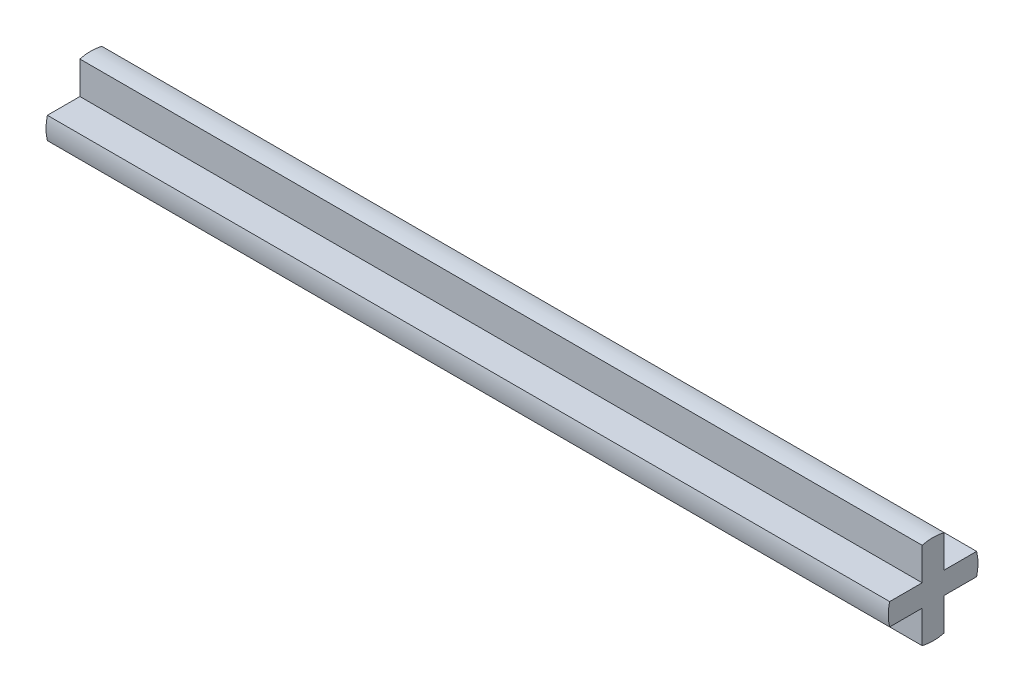
SolidWorks part; units mm, degrees
ref_plane "前视基准面" through (0, 0, 0) normal (0, 0, 1) x (1, 0, 0)
ref_plane "上视基准面" through (0, 0, 0) normal (0, 1, 0) x (1, 0, 0)
ref_plane "右视基准面" through (0, 0, 0) normal (1, 0, 0) x (0, 0, -1)
sketch "草图1" plane through (0, 0, 0) normal (1, 0, 0) x (0, 0, -1)
  circle A0 centre (0, 0) radius 2.45
extrude "凸台-拉伸1" add sketch "草图1" along normal mid plane 46
sketch "草图2" plane through (23, 0, 0) normal (1, 0, 0) x (0, 0, -1)
  line L0 (-3, 0.6) -> (-0.6, 0.6)
  line L1 (0.6, -3) -> (-0.6, -3)
  line L2 (3, -0.6) -> (3, 0.6)
  line L3 (0.6, 3) -> (-0.6, 3)
  line L4 (-3, -0.6) -> (-3, 0.6)
  line L5 (3, -3) -> (-3, 3) construction
  line L6 (3, 3) -> (-3, -3) construction
  line L7 (-0.6, 0.6) -> (-0.6, 3)
  line L8 (0.6, 0.6) -> (0.6, 3)
  line L9 (0.6, 0.6) -> (3, 0.6)
  line L10 (-0.6, -0.6) -> (-3, -0.6)
  line L11 (-0.6, -0.6) -> (-0.6, -3)
  line L12 (0.6, -0.6) -> (0.6, -3)
  line L13 (0.6, -0.6) -> (3, -0.6)
  point P0 (0, 0)
  point P17 (0, 0)
  point P19 (0, 0)
  point P20 (0, 0)
  point P21 (0, 0)
  point P22 (0, 0)
  point P23 (0, 0)
  point P24 (0, 0)
extrude "切除-拉伸1" cut sketch "草图2" against normal through all flip side to cut
